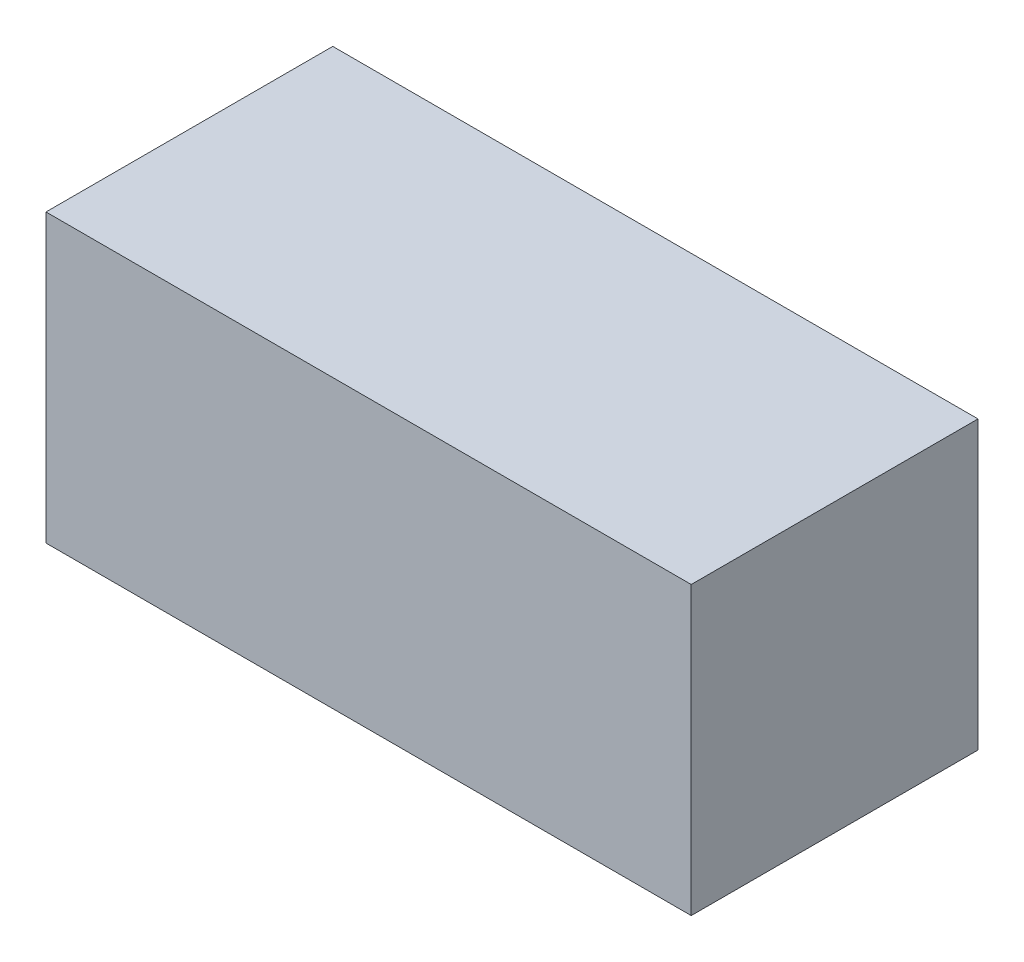
SolidWorks part; units mm, degrees
ref_plane "Front Plane" through (0, 0, 0) normal (0, 0, 1) x (1, 0, 0)
ref_plane "Top Plane" through (0, 0, 0) normal (0, 1, 0) x (1, 0, 0)
ref_plane "Right Plane" through (0, 0, 0) normal (1, 0, 0) x (0, 0, -1)
sketch "Sketch1" plane through (0, 0, 0) normal (0, 0, 1) x (1, 0, 0)
  line L1 (-22.5, 10) -> (22.5, 10)
  line L2 (-22.5, 10) -> (-22.5, -10)
  line L3 (-22.5, -10) -> (22.5, -10)
  line L4 (22.5, 10) -> (22.5, -10)
  line L5 (-22.5, 10) -> (22.5, -10) construction
  line L6 (-22.5, -10) -> (22.5, 10) construction
  point P0 (0, 0)
  dimension "D1" = 45
  dimension "D2" = 20
extrude "Boss-Extrude1" add sketch "Sketch1" along normal blind 20
